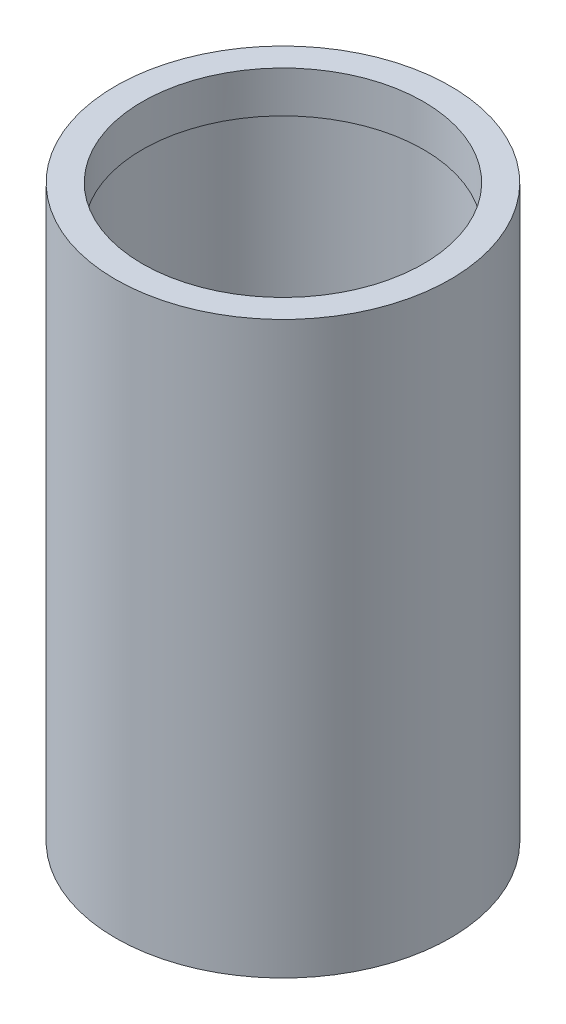
SolidWorks part; units mm, degrees
material "Ceramic Porcelain"
ref_plane "Front Plane" through (0, 0, 0) normal (0, 0, 1) x (1, 0, 0)
ref_plane "Top Plane" through (0, 0, 0) normal (0, 1, 0) x (1, 0, 0)
ref_plane "Right Plane" through (0, 0, 0) normal (1, 0, 0) x (0, 0, -1)
sketch "Sketch1" plane through (0, 0, 0) normal (0, 1, 0) x (1, 0, 0)
  circle A0 centre (0, 0) radius 5.1308
  dimension "D1" = 10.2616
extrude "Boss-Extrude1" add sketch "Sketch1" along normal blind 17.4752
sketch "Sketch2" plane through (0, 0, 0) normal (0, -1, 0) x (1, 0, 0)
  circle A0 centre (0, 0) radius 4.3053
  dimension "D1" = 8.6106
extrude "Cut-Extrude1" cut sketch "Sketch2" against normal blind 25.0952
sketch "Sketch3" plane through (0, 0, 0) normal (0, -1, 0) x (1, 0, 0)
  circle A0 centre (0, 0) radius 4.3663
  dimension "D1" = 8.7325
extrude "Cut-Extrude2" cut sketch "Sketch3" against normal blind 16.2052
